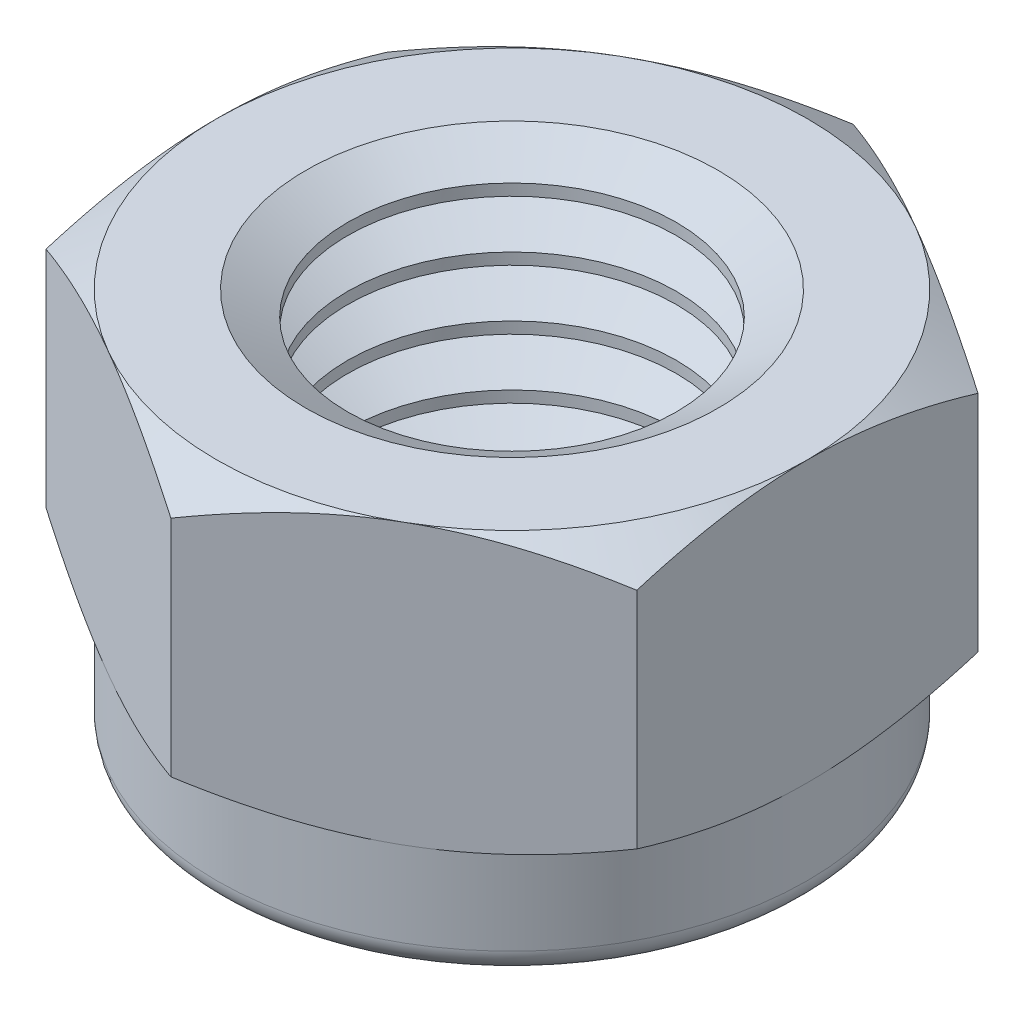
SolidWorks part; units mm, degrees
ref_plane "Front Plane" through (0, 0, 0) normal (0, 0, 1) x (1, 0, 0)
ref_plane "Top Plane" through (0, 0, 0) normal (0, 1, 0) x (1, 0, 0)
ref_plane "Right Plane" through (0, 0, 0) normal (1, 0, 0) x (0, 0, -1)
sketch "Sketch1" plane through (0, 0, 0) normal (0, 1, 0) x (1, 0, 0)
  line L0 (0, 0) -> (0, 7.2517)
  line L1 (0, 0) -> (0, -7.2517)
  line L3 (0, -7.2517) -> (6.2802, -3.6258)
  line L4 (6.2802, -3.6258) -> (6.2802, 3.6259)
  line L5 (6.2802, 3.6259) -> (0, 7.2517)
  line L6 (0, 7.2517) -> (-6.2802, 3.6258)
  line L7 (-6.2802, 3.6258) -> (-6.2802, -3.6259)
  line L8 (-6.2802, -3.6259) -> (0, -7.2517)
  circle A0 centre (0, 0) radius 3.4925
  circle A1 centre (0, 0) radius 6.2802 construction
extrude "Boss-Extrude1" add sketch "Sketch1" along normal blind 5.9436 contours A0 L0 L6 L7 L8 L1 | A0 L1 L3 L4 L5 L0
sketch "Sketch2" plane through (0, 0, 0) normal (0, -1, 0) x (1, 0, 0)
  circle A0 centre (0, 0) radius 6.2802
  circle A1 centre (0, 0) radius 3.4925
extrude "Boss-Extrude2" add sketch "Sketch2" along normal blind 2.3114
fillet "Fillet2" radius 0.508 1 edges at (0, -2.3114, -6.2802)
sketch "Sketch3" plane through (0, 0, 0) normal (1, 0, 0) x (0, 0, -1)
  line L0 (-7.2517, 0) -> (-6.2802, 0)
  line L1 (-6.2802, 0) -> (-7.2517, 0.5931)
  line L2 (-7.2517, 5.9436) -> (-7.2517, 0) construction
  line L3 (-7.2517, 5.9436) -> (-6.2802, 5.9436)
  line L4 (-7.2517, 5.9436) -> (-3.6258, 5.9436) construction
  line L5 (-6.2802, 5.9436) -> (-7.2517, 5.3554)
  line L6 (-7.2517, 0) -> (-7.2517, 0.5931)
  line L7 (-7.2517, 5.9436) -> (-7.2517, 5.3554)
  line L8 (-7.2517, 5.3554) -> (-7.8659, 5.3554)
  line L9 (-7.8659, 5.3554) -> (-7.8659, 6.0978)
  line L10 (-7.8659, 6.0978) -> (-7.2517, 5.9436)
  line L11 (-7.2517, 0.5931) -> (-8.2835, 0.5931)
  line L12 (-8.2835, 0.5931) -> (-8.2835, -0.7382)
  line L13 (-8.2835, -0.7382) -> (-6.2802, 0)
  line L14 (0, 0) -> (0, 4.5618) construction
  line L15 (-3.4925, 5.9436) -> (-4.3815, 5.9436)
  line L16 (-4.3815, 5.9436) -> (-3.4925, 5.4303)
  line L17 (-3.4925, 5.9436) -> (-3.4925, -2.3114) construction
  line L18 (-4.3815, 5.9436) -> (-3.3916, 6.5151)
  line L19 (-4.3815, 5.9436) -> (-3.4842, 5.4256)
  line L20 (-4.3815, 5.9436) -> (-3.2945, 5.316)
  line L21 (-3.2945, 5.316) -> (-3.3916, 6.5151)
  line L22 (-4.3815, 4.6736) -> (-3.3916, 5.2451)
  line L23 (-3.2945, 4.046) -> (-3.3916, 5.2451)
  line L24 (-4.3815, 4.6736) -> (-3.4925, 4.1603)
  line L25 (-4.3815, 4.6736) -> (-3.4842, 4.1556)
  line L26 (-4.3815, 4.6736) -> (-3.2945, 4.046)
  line L27 (-4.3815, 3.4036) -> (-3.3916, 3.9751)
  line L28 (-3.2945, 2.776) -> (-3.3916, 3.9751)
  line L29 (-4.3815, 3.4036) -> (-3.4925, 2.8903)
  line L30 (-4.3815, 3.4036) -> (-3.4842, 2.8856)
  line L31 (-4.3815, 3.4036) -> (-3.2945, 2.776)
  line L32 (-4.3815, 2.1336) -> (-3.3916, 2.7051)
  line L33 (-3.2945, 1.506) -> (-3.3916, 2.7051)
  line L34 (-4.3815, 2.1336) -> (-3.4925, 1.6203)
  line L35 (-4.3815, 2.1336) -> (-3.4842, 1.6156)
  line L36 (-4.3815, 2.1336) -> (-3.2945, 1.506)
  line L37 (-4.3815, 0.8636) -> (-3.3916, 1.4351)
  line L38 (-3.2945, 0.236) -> (-3.3916, 1.4351)
  line L39 (-4.3815, 0.8636) -> (-3.4925, 0.3503)
  line L40 (-4.3815, 0.8636) -> (-3.4842, 0.3456)
  line L41 (-4.3815, 0.8636) -> (-3.2945, 0.236)
  line L42 (-4.3815, -0.4064) -> (-3.3916, 0.1651)
  line L43 (-3.2945, -1.034) -> (-3.3916, 0.1651)
  line L44 (-4.3815, -0.4064) -> (-3.4925, -0.9197)
  line L45 (-4.3815, -0.4064) -> (-3.4842, -0.9244)
  line L46 (-4.3815, -0.4064) -> (-3.2945, -1.034)
  line L47 (-4.3815, -1.6764) -> (-3.3916, -1.1049)
  line L48 (-3.2945, -2.304) -> (-3.3916, -1.1049)
  line L49 (-4.3815, -1.6764) -> (-3.4925, -2.1897)
  line L50 (-4.3815, -1.6764) -> (-3.4842, -2.1944)
  line L51 (-4.3815, -1.6764) -> (-3.2945, -2.304)
  dimension "D1" = 7
revolve "Cut-Revolve1" cut sketch "Sketch3" angle 360 about L14
sketch "Sketch4" plane through (0, -2.3114, 0) normal (0, -1, 0) x (1, 0, 0)
  circle A0 centre (0, 0) radius 3.4925
  circle A1 centre (0, 0) radius 4.6355
extrude "Cut-Extrude1" cut sketch "Sketch4" against normal blind 0.254
sketch "Sketch6" plane through (0, -2.0574, 0) normal (0, -1, 0) x (1, 0, 0)
  circle A0 centre (0, 0) radius 3.4925
  circle A1 centre (0, 0) radius 4.6355
extrude "Boss-Extrude3" add sketch "Sketch6" against normal blind 1.778
